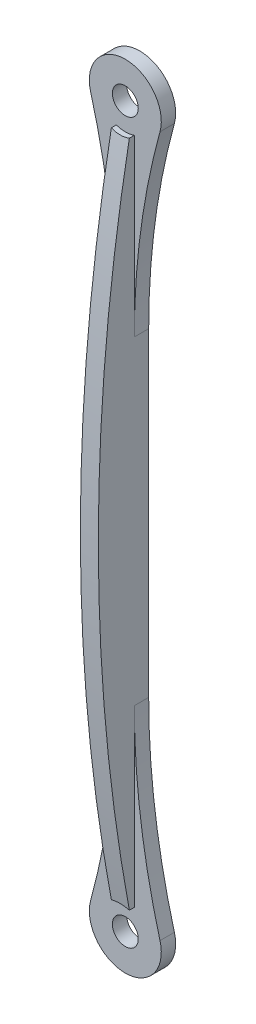
SolidWorks part; units mm, degrees
ref_plane "Front Plane" through (0, 0, 0) normal (0, 0, 1) x (1, 0, 0)
ref_plane "Top Plane" through (0, 0, 0) normal (0, 1, 0) x (1, 0, 0)
ref_plane "Right Plane" through (0, 0, 0) normal (1, 0, 0) x (0, 0, -1)
sketch "Sketch1" plane through (0, 0, 0) normal (0, 0, 1) x (1, 0, 0)
  line L0 (-1.5875, 91.6804) -> (-1.5875, 35.3196)
  line L1 (1.5875, 91.6804) -> (1.5875, 35.3196)
  arc A0 (-6.1232, 1.6819) -> (6.1232, 1.6819) centre (0, 0) ccw
  arc A1 (6.1232, 125.3181) -> (-6.1232, 125.3181) centre (0, 127) ccw
  arc A2 (-6.1232, 125.3181) -> (-1.5875, 91.6804) centre (-128.5875, 91.6804) cw
  arc A3 (-6.1232, 1.6819) -> (-1.5875, 35.3196) centre (-128.5875, 35.3196) ccw
  arc A4 (6.1232, 1.6819) -> (1.5875, 35.3196) centre (128.5875, 35.3196) cw
  arc A5 (6.1232, 125.3181) -> (1.5875, 91.6804) centre (128.5875, 91.6804) ccw
  point P15 (0, 0)
  point P16 (0, 0)
  point P17 (-1.3984, 14.3082)
  dimension "D1" = 6.35
  dimension "D4" = 127
  dimension "D2" = 127
  dimension "D3" = 3.175
extrude "Boss-Extrude1" add sketch "Sketch1" along normal blind 2.54
sketch "Sketch3" plane through (0, 0, 0) normal (1, 0, 0) x (0, 0, -1)
  line L0 (-2.54, 0) -> (-2.54, 127)
  line L2 (-2.54, 125.3181) -> (-2.54, 91.6804) construction
  line L3 (-2.54, 35.3196) -> (-2.54, 91.6804) construction
  arc A0 (-2.54, 127) -> (-2.54, 0) centre (311.785, 63.5) ccw
  point P3 (-2.54, 63.5)
  point P4 (-8.8338, 62.1072)
  point P9 (-2.54, 63.5)
  point P10 (-8.89, 63.5)
  dimension "D2" = 6.35
  dimension "D1" = 127
extrude "Boss-Extrude2" add sketch "Sketch3" along normal mid plane 3.175
sketch "Sketch4" plane through (0, 0, 2.54) normal (0, 0, 1) x (1, 0, 0)
  line L0 (1.5875, 127) -> (-1.5875, 127) construction
  circle A0 centre (0, 0) radius 4.7625
  circle A1 centre (0, 127) radius 4.7625
  dimension "D1" = 9.525
extrude "Cut-Extrude1" cut sketch "Sketch4" along normal through all
sketch "Sketch5" plane through (0, 0, 2.54) normal (0, 0, 1) x (1, 0, 0)
  circle A0 centre (0, 0) radius 2.286
  circle A1 centre (0, 127) radius 2.286
  dimension "D1" = 4.572
extrude "Cut-Extrude2" cut sketch "Sketch5" against normal through all
